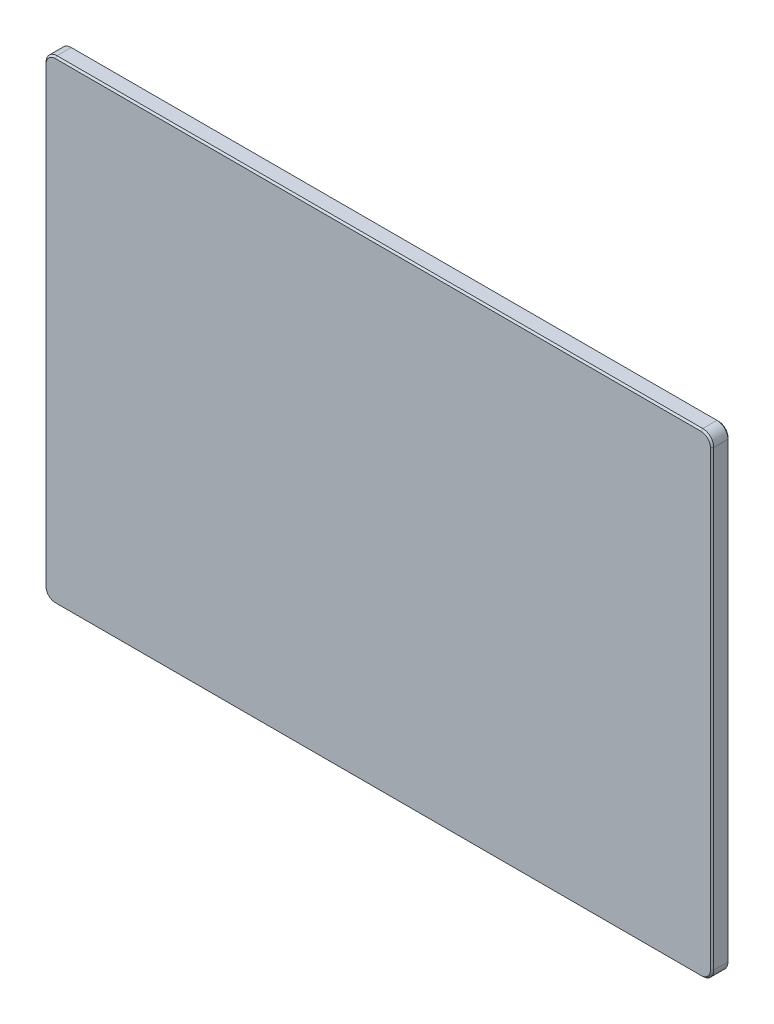
SolidWorks part; units mm, degrees
ref_plane "Front" through (0, 0, 0) normal (0, 0, 1) x (1, 0, 0)
ref_plane "Top" through (0, 0, 0) normal (0, 1, 0) x (1, 0, 0)
ref_plane "Right" through (0, 0, 0) normal (1, 0, 0) x (0, 0, -1)
ref_plane "Plane1" through (0, 0, 8) normal (0, 0, 1) x (1, 0, 0)
sketch "Sketch1" plane through (0, 0, 8) normal (0, 0, 1) x (1, 0, 0)
  line L0 (-152.65, -108.5) -> (152.65, -108.5)
  line L1 (152.65, -108.5) -> (152.65, 108.5)
  line L2 (152.65, 108.5) -> (-152.65, 108.5)
  line L3 (-152.65, 108.5) -> (-152.65, -108.5)
extrude "Boss-Extrude1" add sketch "Sketch1" against normal blind 8
fillet "Fillet1" radius 5 4 edges at (152.65, 108.5, 4) (152.65, -108.5, 4) (-152.65, 108.5, 4) (-152.65, -108.5, 4)
chamfer "Chamfer1" distance 0.75 angle 45 16 edges at (0, 108.5, 8) (-151.1855, 107.0355, 8) (151.1855, 107.0355, 8) (-152.65, 0, 8) (152.65, 0, 8) (-151.1855, -107.0355, 8) (151.1855, -107.0355, 8) (0, -108.5, 8) (0, 108.5, 0) (-151.1855, 107.0355, 0) (151.1855, 107.0355, 0) (-152.65, 0, 0) (152.65, 0, 0) (-151.1855, -107.0355, 0) (151.1855, -107.0355, 0) (0, -108.5, 0)
